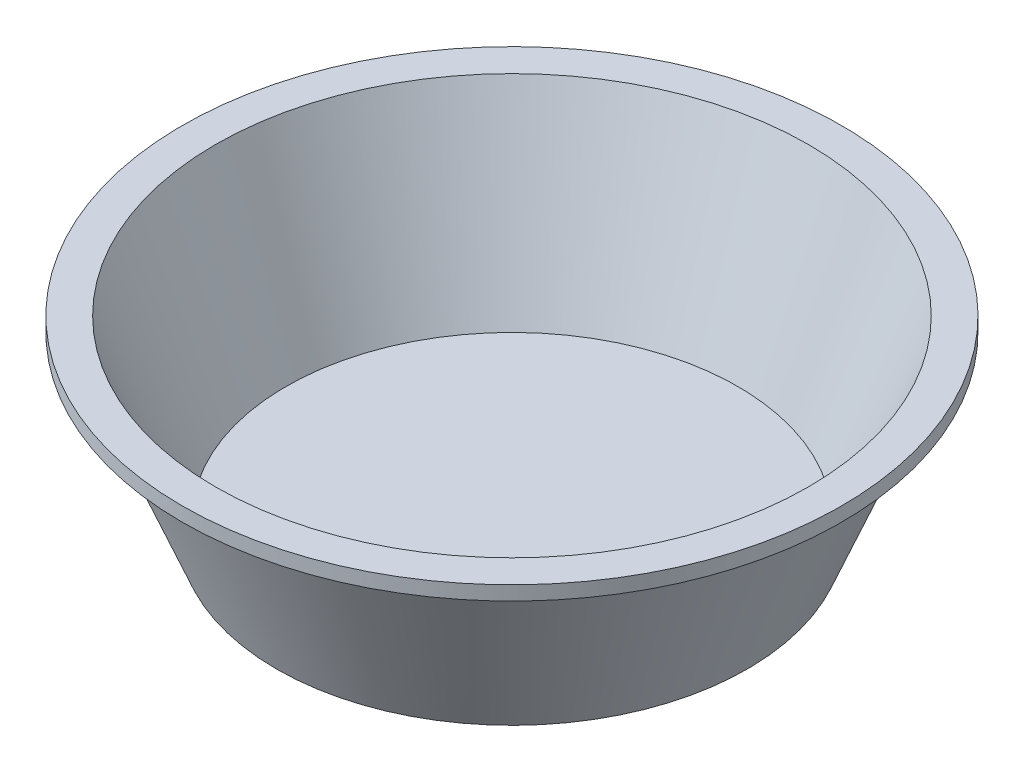
SolidWorks part; units mm, degrees
ref_plane "Front Plane" through (0, 0, 0) normal (0, 0, 1) x (1, 0, 0)
ref_plane "Top Plane" through (0, 0, 0) normal (0, 1, 0) x (1, 0, 0)
ref_plane "Right Plane" through (0, 0, 0) normal (1, 0, 0) x (0, 0, -1)
sketch "Sketch1" plane through (0, 0, 0) normal (0, 0, 1) x (1, 0, 0)
  line L0 (0, 0) -> (50, 0)
  line L1 (50, 0) -> (65, 37)
  line L2 (65, 37) -> (70, 37)
  line L3 (70, 37) -> (70, 40)
  line L4 (70, 40) -> (62.9791, 40)
  line L5 (62.9791, 40) -> (47.9791, 3)
  line L6 (47.9791, 3) -> (0, 3)
  line L7 (0, 3) -> (0, 0)
  dimension "D1" = 65
  dimension "D2" = 50
  dimension "D3" = 3
  dimension "D4" = 3
  dimension "D5" = 3
  dimension "D6" = 5
  dimension "D7" = 40
revolve "Revolve1" add sketch "Sketch1" angle 360 about L7
